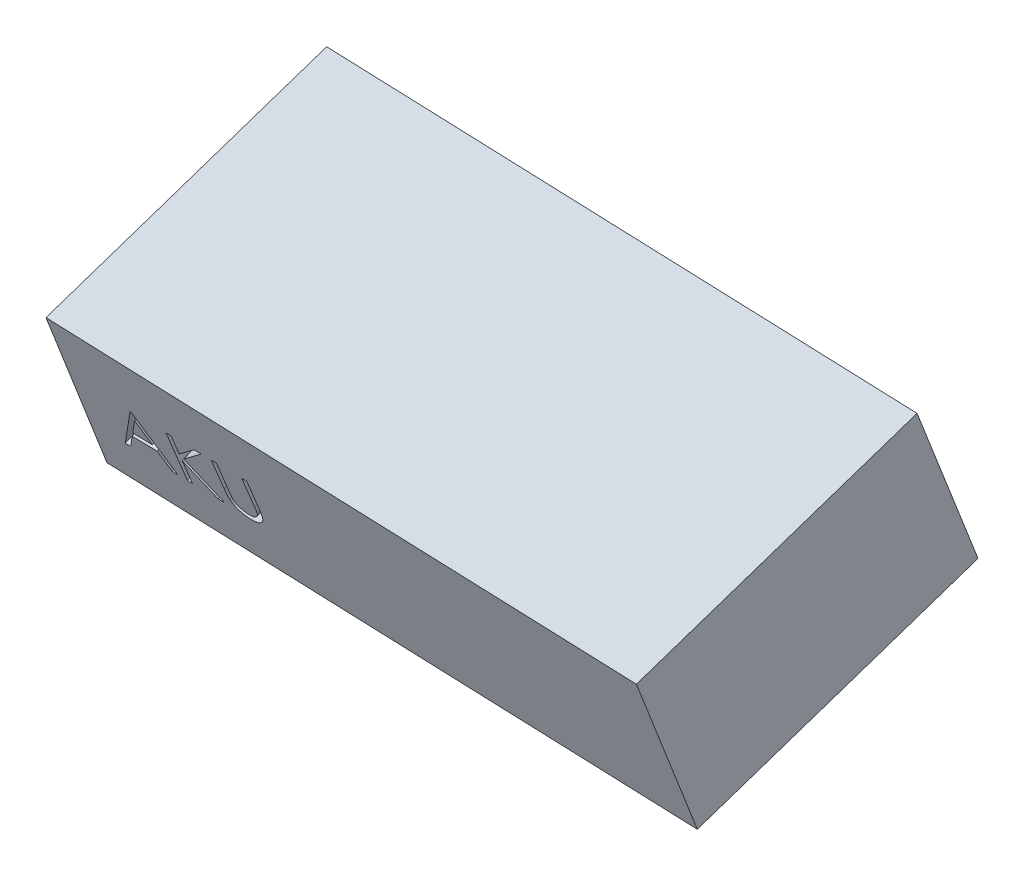
SolidWorks part; units mm, degrees
ref_plane "Płaszczyzna przednia" through (0, 0, 0) normal (0, 0, 1) x (1, 0, 0)
ref_plane "Płaszczyzna górna" through (0, 0, 0) normal (0, 1, 0) x (1, 0, 0)
ref_plane "Płaszczyzna prawa" through (0, 0, 0) normal (1, 0, 0) x (0, 0, -1)
sketch "Szkic1" plane through (1.4792, 39.1515, 16.1872) normal (0.0349, 0.9236, 0.3818) x (-0.998, 0.0521, -0.0349)
  line L0 (149.3532, 20.8246) -> (163.3432, 21.3531) construction
  line L1 (162.6636, 39.3403) -> (148.6736, 38.8117) construction
  line L2 (142.1912, 20.554) -> (179.1648, 21.9509)
  line L3 (179.1648, 39.9637) -> (142.1912, 38.5668)
  line L5 (142.1912, 38.5668) -> (142.1912, 20.554)
  line L8 (179.1648, 21.9509) -> (179.1648, 39.9637)
  dimension "D1" = 37
extrude "Dodanie-wyciągnięcie2" add sketch "Szkic1" along normal up to surface (11 mm away)
sketch "Szkic4" plane through (-0.4782, -12.6573, 30.6574) normal (-0.0144, -0.3816, 0.9242) x (0.9999, -0.0055, 0.0133)
  text T0 "AKU"
extrude "Wytnij-wyciągnięcie3" cut sketch "Szkic4" against normal blind 3
sketch "Szkic5" plane through (-0.2187, -5.7889, 14.0213) normal (0.0144, 0.3816, -0.9242) x (-0.9999, 0.0055, -0.0133)
  text T0 "AKU"
extrude "Wytnij-wyciągnięcie4" cut sketch "Szkic5" against normal blind 3
sketch "Szkic6" plane through (1.863, 49.3107, 20.3876) normal (0.0349, 0.9236, 0.3818) x (0.9994, -0.0322, -0.0133)
  circle A0 centre (-171.5784, -21.4583) radius 3.6879
